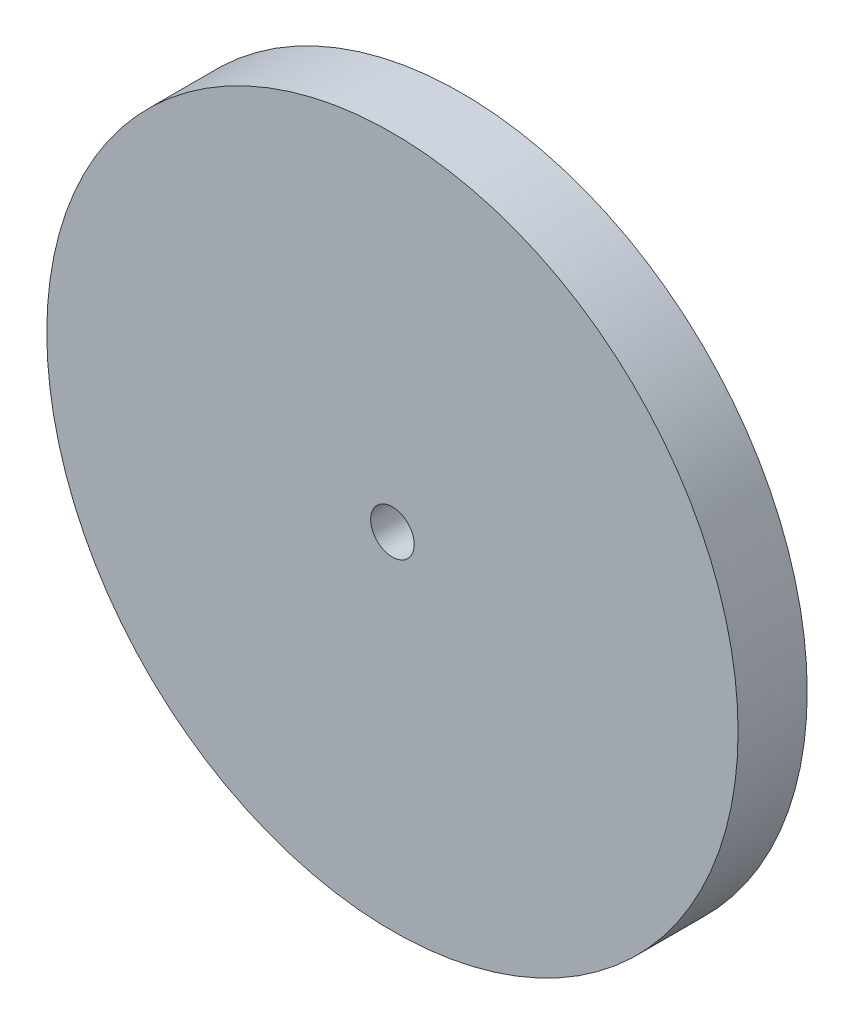
SolidWorks part; units mm, degrees
ref_plane "Front Plane" through (0, 0, 0) normal (0, 0, 1) x (1, 0, 0)
ref_plane "Top Plane" through (0, 0, 0) normal (0, 1, 0) x (1, 0, 0)
ref_plane "Right Plane" through (0, 0, 0) normal (1, 0, 0) x (0, 0, -1)
sketch "Sketch1" plane through (0, 0, 0) normal (0, 0, 1) x (1, 0, 0)
  circle A0 centre (0, 0) radius 63.5
  circle A1 centre (0, 0) radius 4
  dimension "D1" = 8
  dimension "D2" = 127
extrude "Boss-Extrude1" add sketch "Sketch1" along normal blind 12.7
